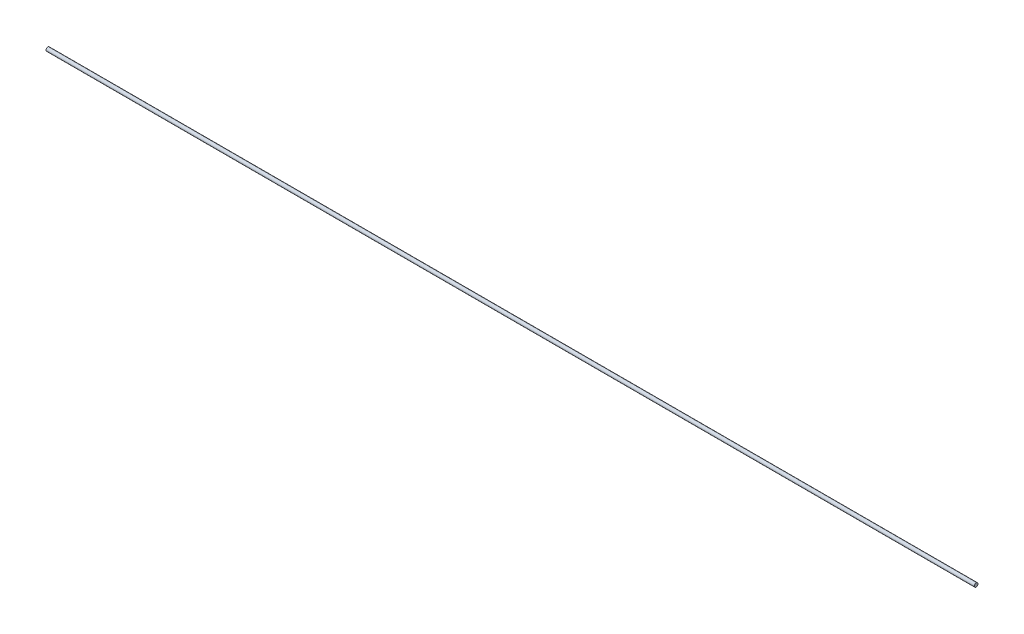
SolidWorks part; units mm, degrees
material "AISI 1020"
ref_plane "Front Plane" through (0, 0, 0) normal (0, 0, 1) x (1, 0, 0)
ref_plane "Top Plane" through (0, 0, 0) normal (0, 1, 0) x (1, 0, 0)
ref_plane "Right Plane" through (0, 0, 0) normal (1, 0, 0) x (0, 0, -1)
sketch "Sketch1" plane through (0, 0, 0) normal (1, 0, 0) x (0, 0, -1)
  circle A0 centre (0, 0) radius 3.175
  dimension "D1" = 6.35
extrude "Boss-Extrude1" add sketch "Sketch1" along normal blind 1593.85
equation "\"OD\"= 1 / 4"
equation "\"L\"= 62.75"
equation "\"D1@Sketch1\"=\"OD\""
equation "\"D1@Boss-Extrude1\"=\"L\""
